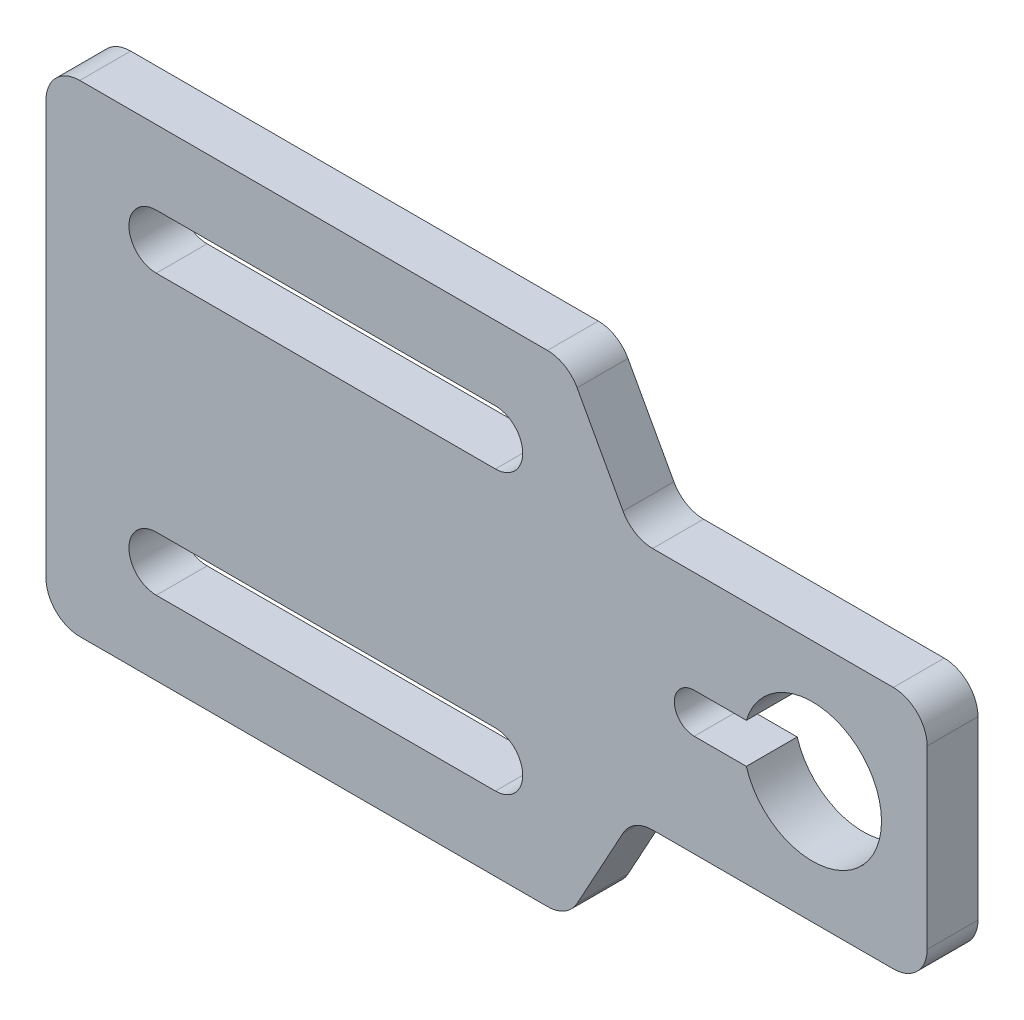
SolidWorks part; units mm, degrees
ref_plane "Front Plane" through (0, 0, 0) normal (0, 0, 1) x (1, 0, 0)
ref_plane "Top Plane" through (0, 0, 0) normal (0, 1, 0) x (1, 0, 0)
ref_plane "Right Plane" through (0, 0, 0) normal (1, 0, 0) x (0, 0, -1)
sketch "Sketch1" plane through (0, 0, 0) normal (0, 0, 1) x (1, 0, 0)
  line L0 (0, 42.0477) -> (0, 3.175)
  line L1 (3.175, 0) -> (47.082, 0)
  line L2 (49.8668, 1.65) -> (54.175, 9.5172)
  line L3 (56.9598, 11.1672) -> (79.5558, 11.1672)
  line L5 (3.175, 45.2227) -> (47.082, 45.2227)
  line L6 (49.8668, 43.5727) -> (54.175, 35.7054)
  line L7 (56.9598, 34.0554) -> (79.5558, 34.0554)
  line L8 (82.7308, 14.3422) -> (82.7308, 30.8804)
  line L9 (65.7544, 24.4815) -> (60.8657, 24.4815)
  line L10 (10.3534, 35.7054) -> (42.193, 35.7054) construction
  line L11 (10.3534, 38.271) -> (42.193, 38.271)
  line L12 (10.3534, 33.1398) -> (42.193, 33.1398)
  line L13 (10.3534, 9.5172) -> (42.193, 9.5172) construction
  line L14 (65.7544, 20.7412) -> (60.8657, 20.7412)
  line L15 (10.3534, 6.9516) -> (42.193, 6.9516)
  line L16 (10.3534, 12.0828) -> (42.193, 12.0828)
  arc A0 (82.7308, 30.8804) -> (79.5558, 34.0554) centre (79.5558, 30.8804) ccw
  arc A1 (82.7308, 14.3422) -> (79.5558, 11.1672) centre (79.5558, 14.3422) cw
  arc A2 (54.175, 9.5172) -> (56.9598, 11.1672) centre (56.9598, 7.9922) cw
  arc A3 (49.8668, 1.65) -> (47.082, 0) centre (47.082, 3.175) cw
  arc A4 (54.175, 35.7054) -> (56.9598, 34.0554) centre (56.9598, 37.2304) ccw
  arc A5 (47.082, 45.2227) -> (49.8668, 43.5727) centre (47.082, 42.0477) cw
  arc A6 (3.175, 45.2227) -> (0, 42.0477) centre (3.175, 42.0477) ccw
  arc A7 (3.175, 0) -> (0, 3.175) centre (3.175, 3.175) cw
  arc A8 (65.7544, 20.7412) -> (65.7544, 24.4815) centre (71.962, 22.6113) ccw
  arc A9 (60.8657, 24.4815) -> (60.8657, 20.7412) centre (60.8657, 22.6113) ccw
  arc A10 (10.3534, 38.271) -> (10.3534, 33.1398) centre (10.3534, 35.7054) ccw
  arc A11 (42.193, 33.1398) -> (42.193, 38.271) centre (42.193, 35.7054) ccw
  arc A12 (10.3534, 6.9516) -> (10.3534, 12.0828) centre (10.3534, 9.5172) cw
  arc A13 (42.193, 12.0828) -> (42.193, 6.9516) centre (42.193, 9.5172) cw
  point P13 (82.7308, 34.0554)
  point P16 (82.7308, 11.1672)
  point P19 (55.0786, 11.1672)
  point P22 (48.9632, 0)
  point P25 (55.0786, 34.0554)
  point P28 (48.9632, 45.2227)
  point P31 (0, 45.2227)
  point P34 (0, 0)
  point P40 (26.2732, 35.7054)
  point P49 (26.2732, 9.5172)
extrude "Extrude1" add sketch "Sketch1" along normal blind 4.7752
